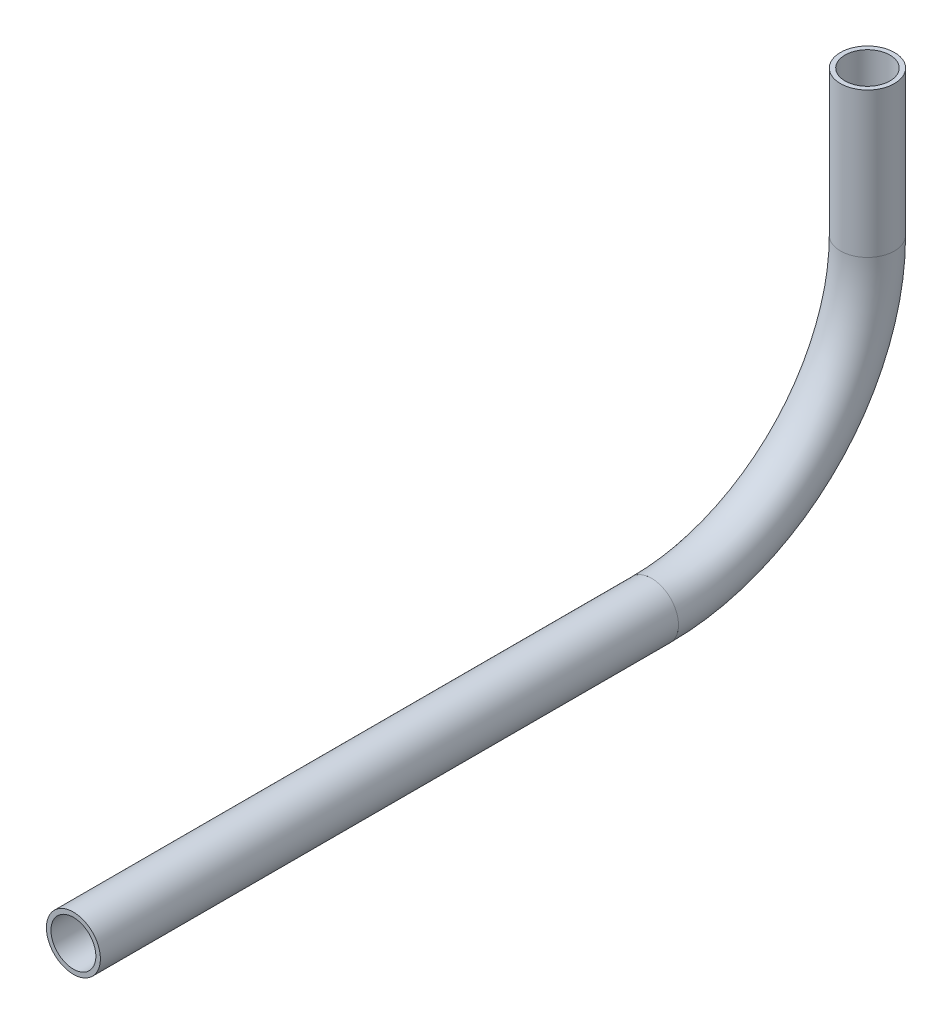
SolidWorks part; units mm, degrees
ref_plane "Front Plane" through (0, 0, 0) normal (0, 0, 1) x (1, 0, 0)
ref_plane "Top Plane" through (0, 0, 0) normal (0, 1, 0) x (1, 0, 0)
ref_plane "Right Plane" through (0, 0, 0) normal (1, 0, 0) x (0, 0, -1)
sketch "Sketch1" plane through (0, 0, 0) normal (1, 0, 0) x (0, 0, -1)
  line L0 (-303.1646, 599.96) -> (-167.159, 599.96)
  line L1 (-116.359, 650.76) -> (-116.359, 684.869)
  arc A0 (-167.159, 599.96) -> (-116.359, 650.76) centre (-167.159, 650.76) ccw
  dimension "D1" = 50.8
other "Pipe 0.5 SCH 40(1)"
ref_plane "Plane1" through (0, 599.96, 303.1646) normal (0, 0, -1) x (0, 1, 0)
sketch "Sketch11" plane through (0, 599.96, 303.1646) normal (0, 0, -1) x (0, 1, 0)
  circle A0 centre (0, 0) radius 5.2832
  circle A1 centre (0, 0) radius 6.35
  point P5 (0, 0)
  dimension "In_dia" = 10.5664
  dimension "Out_dia" = 12.7
